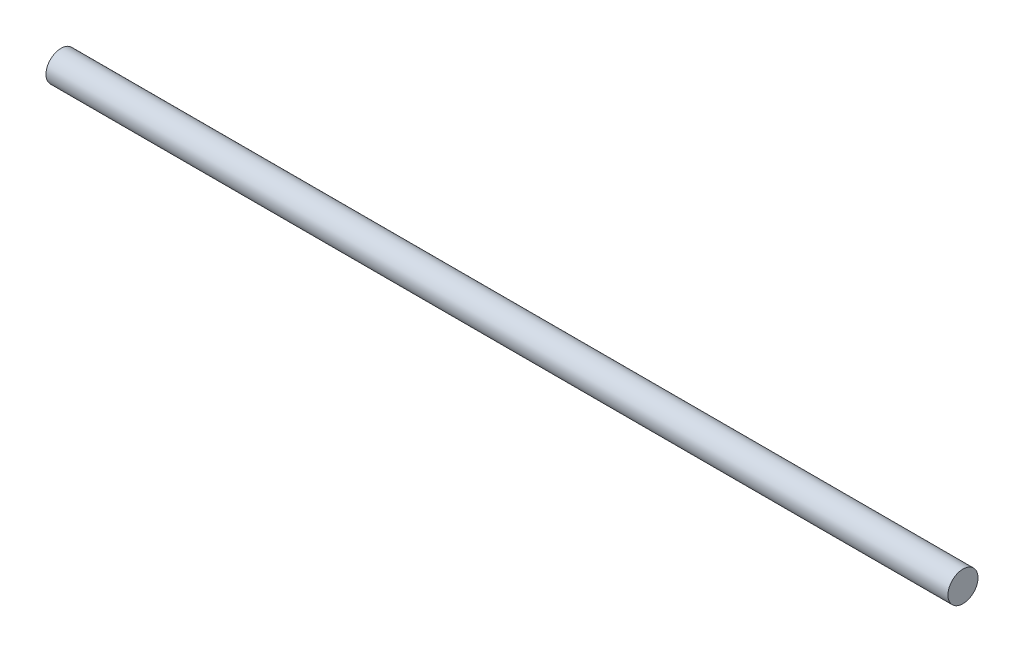
SolidWorks part; units mm, degrees
ref_plane "前视基准面" through (0, 0, 0) normal (0, 0, 1) x (1, 0, 0)
ref_plane "上视基准面" through (0, 0, 0) normal (0, 1, 0) x (1, 0, 0)
ref_plane "右视基准面" through (0, 0, 0) normal (1, 0, 0) x (0, 0, -1)
other "Configuration Table"
sketch "草图1" plane through (0, 0, 0) normal (1, 0, 0) x (0, 0, -1)
  circle A0 centre (0, 0) radius 2
  dimension "D1" = 4
extrude "凸台-拉伸1" add sketch "草图1" along normal blind 120
